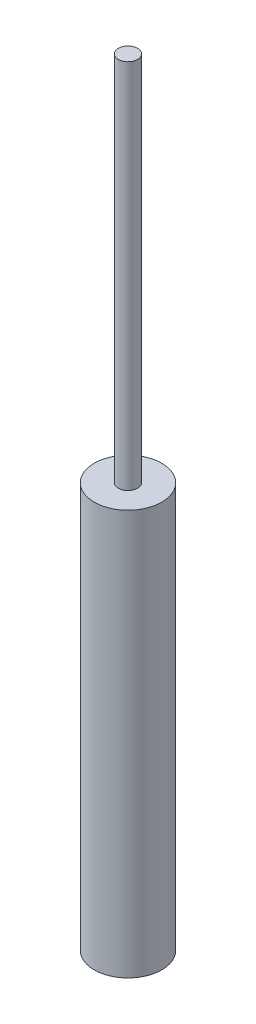
SolidWorks part; units mm, degrees
material "ABS PC"
ref_plane "Front Plane" through (0, 0, 0) normal (0, 0, 1) x (1, 0, 0)
ref_plane "Top Plane" through (0, 0, 0) normal (0, 1, 0) x (1, 0, 0)
ref_plane "Right Plane" through (0, 0, 0) normal (1, 0, 0) x (0, 0, -1)
sketch "Sketch1" plane through (0, 0, 0) normal (0, 1, 0) x (1, 0, 0)
  circle A0 centre (0, 0) radius 2.5
  dimension "D1" = 5
extrude "Boss-Extrude1" add sketch "Sketch1" along normal mid plane 30
sketch "Sketch2" plane through (0, 15, 0) normal (0, 1, 0) x (1, 0, 0)
  circle A0 centre (0, 0) radius 0.715
  dimension "D1" = 1.43
extrude "Boss-Extrude2" add sketch "Sketch2" along normal blind 27.5
